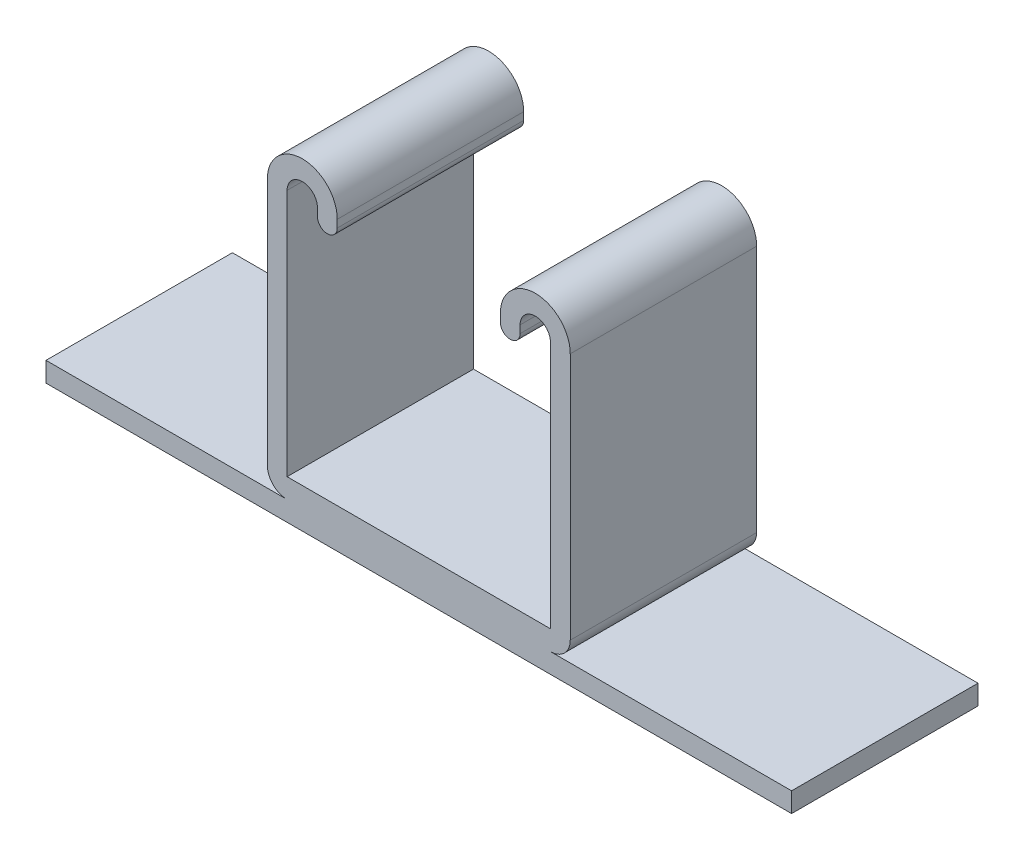
SolidWorks part; units mm, degrees
ref_plane "Plane1" through (0, 0, 0) normal (0, 0, 1) x (1, 0, 0)
ref_plane "Plane2" through (0, 0, 0) normal (0, 1, 0) x (1, 0, 0)
ref_plane "Plane3" through (0, 0, 0) normal (1, 0, 0) x (0, 0, -1)
sketch "Sketch1" plane through (0, 0, 0) normal (0, 0, 1) x (1, 0, 0)
  line L0 (-20.6375, 26.8351) -> (-20.6375, -6.9596)
  line L2 (20.6375, -6.9596) -> (20.6375, 26.8351)
  line L3 (11.1125, 26.8351) -> (11.1125, 25.8)
  line L4 (-11.1125, 26.8351) -> (-11.1125, 25.8)
  line L5 (-13.8049, 26.8351) -> (-13.8049, 25.8)
  line L6 (-17.9451, 26.8351) -> (-17.9451, -6.9596)
  line L7 (-17.9451, -6.9596) -> (17.9451, -6.9596)
  line L8 (17.9451, -6.9596) -> (17.9451, 26.8351)
  line L9 (13.8049, 26.8351) -> (13.8049, 25.8)
  line L10 (-25.4, 31.5976) -> (25.4, 31.5976) construction
  line L11 (-12.8524, 24.4538) -> (12.8524, 24.4538) construction
  line L12 (17.9451, -9.652) -> (50.8, -9.652)
  line L13 (50.8, -9.652) -> (50.8, -12.3444)
  line L14 (50.8, -12.3444) -> (-50.8, -12.3444)
  line L15 (-50.8, -12.3444) -> (-50.8, -9.652)
  line L16 (-50.8, -9.652) -> (-17.9451, -9.652)
  arc A0 (20.6375, 26.8351) -> (11.1125, 26.8351) centre (15.875, 26.8351) ccw
  arc A1 (-20.6375, 26.8351) -> (-11.1125, 26.8351) centre (-15.875, 26.8351) cw
  arc A2 (-17.9451, -9.652) -> (-20.6375, -6.9596) centre (-17.9451, -6.9596) cw
  arc A3 (17.9451, -9.652) -> (20.6375, -6.9596) centre (17.9451, -6.9596) ccw
  arc A4 (-17.9451, 26.8351) -> (-13.8049, 26.8351) centre (-15.875, 26.8351) cw
  arc A5 (17.9451, 26.8351) -> (13.8049, 26.8351) centre (15.875, 26.8351) ccw
  arc A6 (11.1125, 25.8) -> (13.8049, 25.8) centre (12.4587, 25.8) ccw
  arc A7 (-11.1125, 25.8) -> (-13.8049, 25.8) centre (-12.4587, 25.8) cw
  dimension "D1" = 2.6924
  dimension "D3" = 20.6375
  dimension "Width" = 41.275
  dimension "D6" = 9.525
  dimension "D7" = 22.225
  dimension "D8" = 31.5976
  dimension "D9" = 7.1437
  dimension "D4" = 2.6924
  dimension "D5" = 2.6924
  dimension "D10" = 50.8
  dimension "D11" = 101.6
  dimension "D2" = 12.3444
  dimension "gauge" = 2.6924
extrude "Base-Extrude" add sketch "Sketch1" along normal mid plane 25.4
equation "\"D3@Sketch1\" = \"Width@Sketch1\" / 2"
equation "\"D7@Sketch1\" = \"Width@Sketch1\" - 2 * \"D6@Sketch1\""
equation "\"D1@Sketch1\" = \"gauge@Sketch1\""
